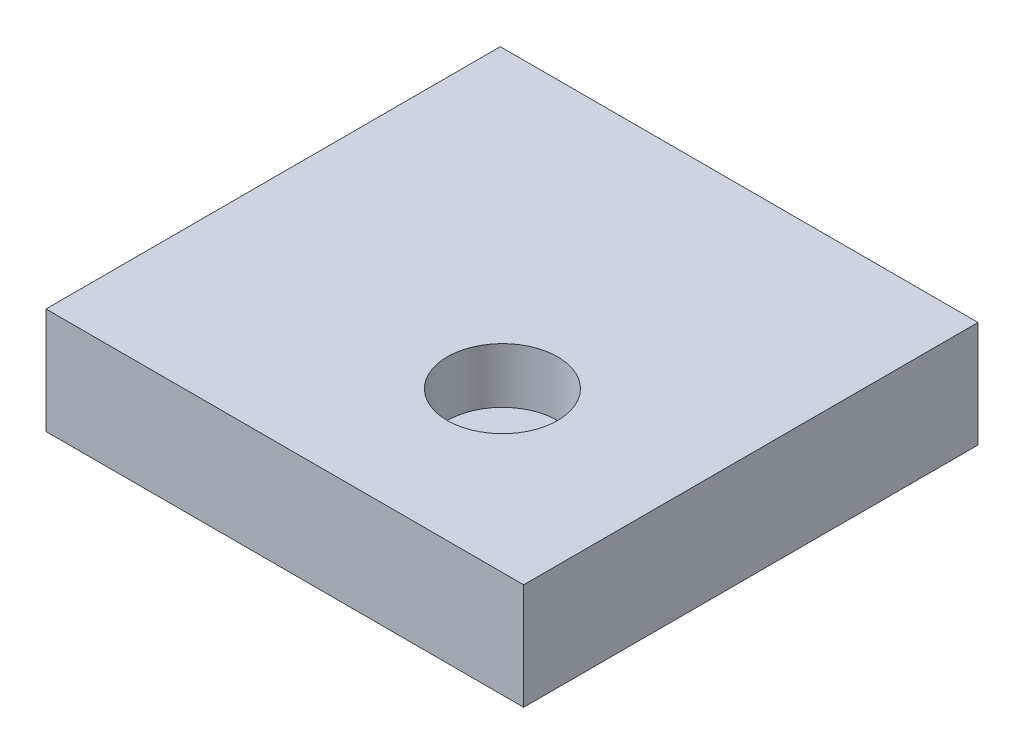
SolidWorks part; units mm, degrees
other "标注1"
sketch "草图3" plane through (0, 5, 29.5) normal (-0.6417, 0.7662, 0.0339) x (0.7661, 0.6384, 0.0747)
ref_plane "前视基准面" through (0, 0, 0) normal (0, 0, 1) x (1, 0, 0)
ref_plane "上视基准面" through (0, 0, 0) normal (0, 1, 0) x (1, 0, 0)
ref_plane "右视基准面" through (0, 0, 0) normal (1, 0, 0) x (0, 0, -1)
other "Configuration Table"
sketch "草图1" plane through (0, 0, 0) normal (0, 1, 0) x (1, 0, 0)
  line L33 (-20, -21.4) -> (0, -21.4)
  line L34 (-20, -21.4) -> (-20, 0)
  line L36 (0, -21.4) -> (0, 0)
  line L37 (-20, 0) -> (0, 0)
  point P0 (-90.6464, 22.0667)
  dimension "D1" = 20
  dimension "D2" = 21.4
extrude "凸台-拉伸1" add sketch "草图1" along normal blind 5
sketch "草图4" plane through (-20, 0, 0) normal (-1, 0, 0) x (0, 0, 1)
  line L1 (21.4, 5) -> (21.4, 0) construction
  line L2 (0, 5) -> (0, 0) construction
  circle A0 centre (16.4, 2.5) radius 0.85
  circle A1 centre (5, 2.5) radius 0.85
  point P6 (21.4, 2.5)
  dimension "D1" = 1.7
  dimension "D2" = 5
  dimension "D3" = 5
extrude "切除-拉伸1" cut sketch "草图4" against normal blind 4 contours A0 | A1
sketch "草图5" plane through (0, 0, 0) normal (0, 0, -1) x (-1, 0, 0)
  line L0 (0, 5) -> (0, 0) construction
  line L1 (20, 5) -> (20, 0) construction
  circle A0 centre (15, 2.5) radius 0.85
  circle A1 centre (5, 2.5) radius 0.85
  point P6 (0, 2.5)
  dimension "D1" = 1.7
  dimension "D2" = 5
  dimension "D3" = 5
extrude "切除-拉伸2" cut sketch "草图5" against normal blind 4 contours A1 | A0
sketch "草图6" plane through (0, 0, 0) normal (1, 0, 0) x (0, 0, -1)
  line L1 (-21.4, 0) -> (0, 0)
  line L2 (-21.4, 0) -> (-21.4, 5)
  line L3 (-21.4, 5) -> (0, 5)
  line L4 (0, 0) -> (0, 5)
extrude "凸台-拉伸2" add sketch "草图6" along normal blind 2.5
sketch "草图7" plane through (0, 5, 0) normal (0, 1, 0) x (1, 0, 0)
  circle A0 centre (-6, -13.9) radius 2.6
  point P3 (0, 0)
  dimension "D1" = 5.2
extrude "切除-拉伸3" cut sketch "草图7" against normal blind 2.6
